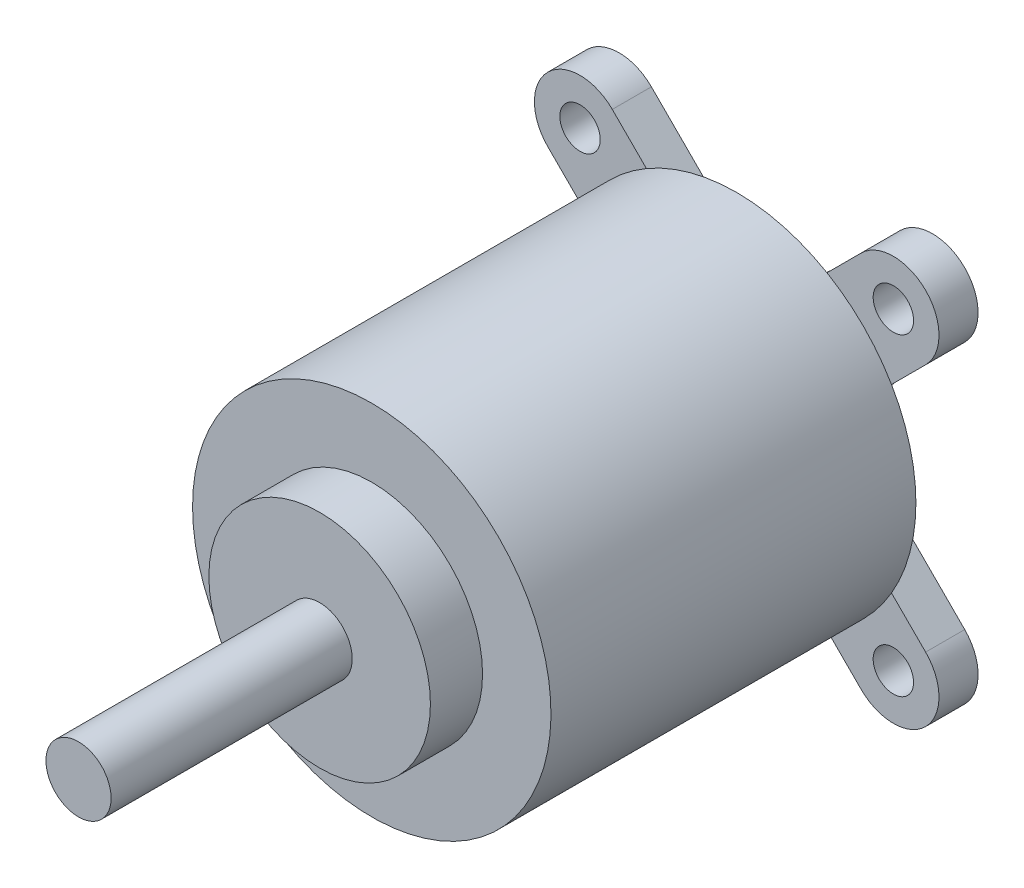
SolidWorks part; units mm, degrees
ref_plane "Front Plane" through (0, 0, 0) normal (0, 0, 1) x (1, 0, 0)
ref_plane "Top Plane" through (0, 0, 0) normal (0, 1, 0) x (1, 0, 0)
ref_plane "Right Plane" through (0, 0, 0) normal (1, 0, 0) x (0, 0, -1)
sketch "Sketch1" plane through (0, 0, 0) normal (0, 0, 1) x (1, 0, 0)
  circle A0 centre (0, 0) radius 13.75
  dimension "D1" = 27.5
extrude "Boss-Extrude1" add sketch "Sketch1" along normal blind 28
sketch "Sketch2" plane through (0, 0, 28) normal (0, 0, 1) x (1, 0, 0)
  circle A0 centre (0, 0) radius 8.5
  dimension "D1" = 17
extrude "Boss-Extrude2" add sketch "Sketch2" along normal blind 4
sketch "Sketch4" plane through (0, 0, 0) normal (0, 0, -1) x (-1, 0, 0)
  line L0 (0, -17) -> (0, 17) construction
  line L1 (-3.5, -17) -> (-3.5, -9.5)
  line L2 (3.5, -17) -> (3.5, -9.5)
  line L3 (17, 0) -> (-17, 0) construction
  line L4 (17, -3.5) -> (9.5, -3.5)
  line L5 (17, 3.5) -> (9.5, 3.5)
  line L6 (-9.5, 3.5) -> (-17, 3.5)
  line L7 (-3.5, 9.5) -> (-3.5, 17)
  line L8 (3.5, 9.5) -> (3.5, 17)
  line L9 (-9.5, -3.5) -> (-17, -3.5)
  arc A0 (-3.5, -17) -> (3.5, -17) centre (0, -17) ccw
  arc A1 (3.5, 17) -> (-3.5, 17) centre (0, 17) ccw
  arc A2 (17, -3.5) -> (17, 3.5) centre (17, 0) ccw
  arc A3 (-17, 3.5) -> (-17, -3.5) centre (-17, 0) ccw
  arc A4 (-3.5, -9.5) -> (-9.5, -3.5) centre (-9.5, -9.5) ccw
  arc A5 (3.5, -9.5) -> (9.5, -3.5) centre (9.5, -9.5) cw
  arc A6 (9.5, 3.5) -> (3.5, 9.5) centre (9.5, 9.5) cw
  arc A7 (-9.5, 3.5) -> (-3.5, 9.5) centre (-9.5, 9.5) ccw
  point P2 (0, 0)
  point P10 (0, 0)
  point P22 (0, 20.5)
  point P24 (0, -20.5)
  point P27 (0, 0)
  point P28 (0, 0)
  point P38 (-3.5, -3.5)
  point P45 (-3.5, 3.5)
  dimension "D2" = 3.5
  dimension "D4" = 7
  dimension "D5" = 6
  dimension "D1" = 41
  dimension "D3" = 7
extrude "Boss-Extrude3" add sketch "Sketch4" along normal blind 3
sketch "Sketch5" plane through (0, 0, -3) normal (0, 0, -1) x (-1, 0, 0)
  circle A0 centre (0, 17) radius 1.55
  circle A1 centre (17, 0) radius 1.55
  circle A2 centre (0, -17) radius 1.55
  circle A3 centre (-17, 0) radius 1.55
  point P12 (0, 0)
  dimension "D2" = 3.1
  dimension "D1" = 17
  dimension "D3" = 4
extrude "Cut-Extrude1" cut sketch "Sketch5" against normal up to surface (3 mm away) up to face at (0, 16.1368, 0)
move or copy body "Body-Move/Copy1" bodies to move or copy 104 copy no rotation origin (0, 0, 0) rotation axis (0, 0, 1) rotation angle 45
sketch "Sketch6" plane through (0, 0, 32) normal (0, 0, 1) x (1, 0, 0)
  circle A0 centre (0, 0) radius 2.5
  dimension "D1" = 5
extrude "Boss-Extrude4" add sketch "Sketch6" along normal blind 18.5
